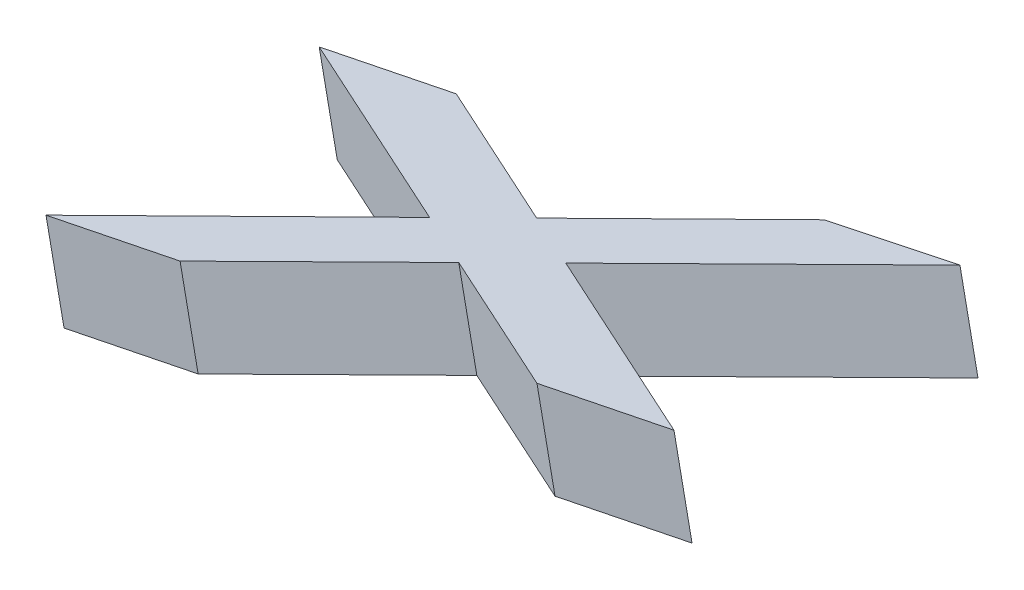
SolidWorks part; units mm, degrees
material "ABS"
ref_plane "Front Plane" through (0, 0, 0) normal (0, 0, 1) x (1, 0, 0)
ref_plane "Top Plane" through (0, 0, 0) normal (0, 1, 0) x (1, 0, 0)
ref_plane "Right Plane" through (0, 0, 0) normal (1, 0, 0) x (0, 0, -1)
sketch "Sketch1" plane through (-2.6105, 12.8318, 0) normal (0.1994, -0.9799, 0) x (-0.9799, -0.1994, 0)
  line L0 (14.5196, -38.6194) -> (39.5245, -52.8063)
  line L3 (78.5686, -66.6891) -> (14.5196, -66.6891) construction
  line L4 (77.4238, -66.6891) -> (53.0558, -52.9138)
  line L8 (28.2444, -66.6891) -> (46.3125, -56.6576)
  line L10 (64.8438, -38.7491) -> (46.2553, -49.0694)
  line L11 (39.5245, -52.8063) -> (14.5196, -66.6891)
  line L12 (46.3125, -56.6576) -> (63.9933, -66.6891)
  line L13 (53.0558, -52.9138) -> (78.5686, -38.7491)
  line L14 (46.2553, -49.0694) -> (27.999, -38.7491)
  line L16 (27.999, -38.7491) -> (14.5196, -38.6194)
  line L17 (78.5686, -38.7491) -> (14.5196, -38.7491) construction
  line L18 (14.5196, -66.6891) -> (28.2444, -66.6891)
  line L19 (78.5686, -38.7491) -> (64.8438, -38.7491)
  line L20 (63.9933, -66.6891) -> (77.4238, -66.6891)
extrude "Boss-Extrude1" add sketch "Sketch1" against normal blind 8.89
